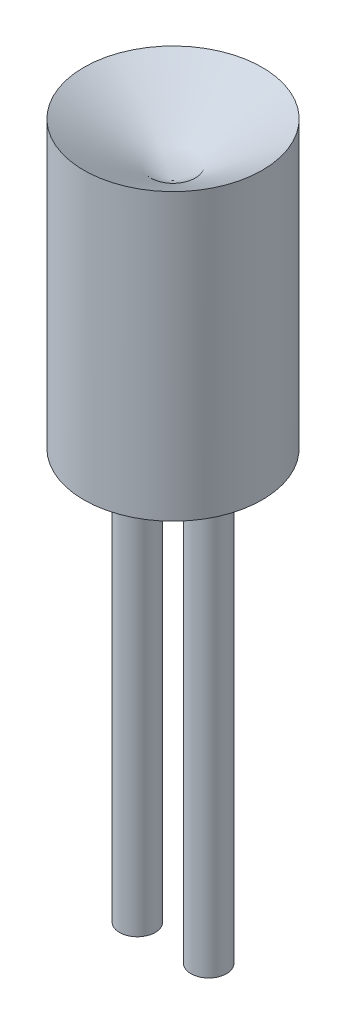
SolidWorks part; units mm, degrees
ref_plane "Front Plane" through (0, 0, 0) normal (0, 0, 1) x (1, 0, 0)
ref_plane "Top Plane" through (0, 0, 0) normal (0, 1, 0) x (1, 0, 0)
ref_plane "Right Plane" through (0, 0, 0) normal (1, 0, 0) x (0, 0, -1)
sketch "Sketch1" plane through (0, 0, 0) normal (0, 1, 0) x (1, 0, 0)
  circle A0 centre (0, 0) radius 2.5
  dimension "D1" = 5
extrude "Boss-Extrude1" add sketch "Sketch1" along normal blind 8
sketch "Sketch2" plane through (0, 0, 0) normal (0, 0, 1) x (1, 0, 0)
  line L0 (0, 8) -> (0, 6.5)
  line L1 (2.5, 8) -> (-2.5, 8) construction
  line L2 (0, 6.5) -> (-2.5, 8)
  line L3 (-2.5, 8) -> (0, 8)
  dimension "D1" = 1.5
revolve "Cut-Revolve2" cut sketch "Sketch2" angle 360 about L0
sketch "Sketch3" plane through (0, 0, 0) normal (0, -1, 0) x (1, 0, 0)
  line L0 (-1, 0) -> (1, 0) construction
  line L1 (0, 0) -> (0, -0.3288) construction
  circle A0 centre (-1, 0) radius 0.5
  circle A1 centre (1, 0) radius 0.5
  point P4 (0, 0)
  dimension "D2" = 1
  dimension "D1" = 2
extrude "Boss-Extrude2" add sketch "Sketch3" along normal blind 12
